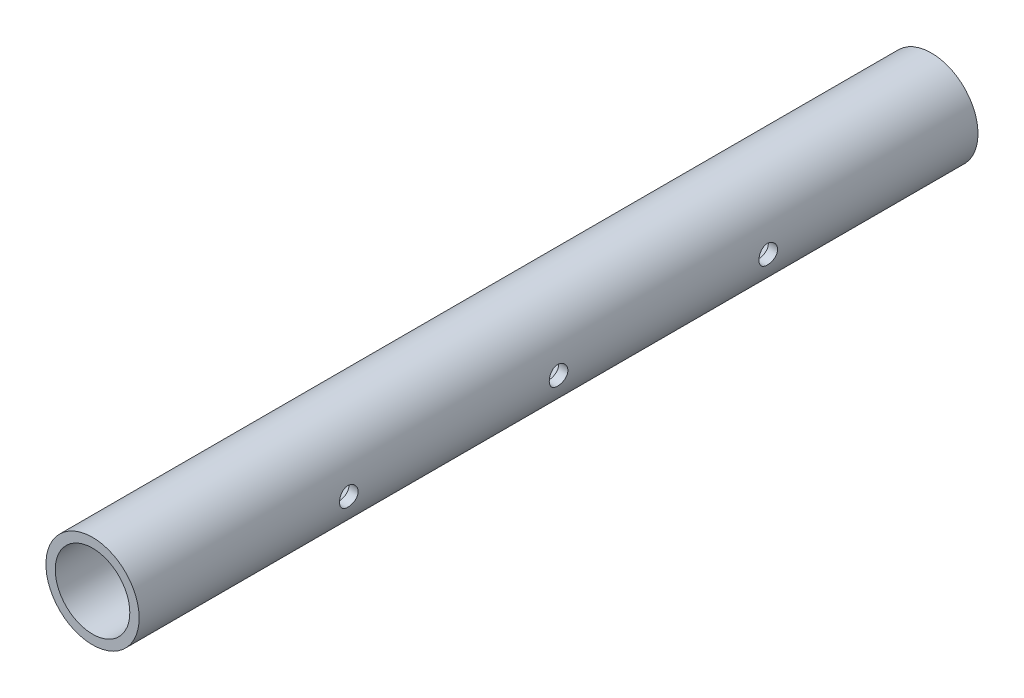
SolidWorks part; units mm, degrees
material "PVC Rigid"
ref_plane "Front Plane" through (0, 0, 0) normal (0, 0, 1) x (1, 0, 0)
ref_plane "Top Plane" through (0, 0, 0) normal (0, 1, 0) x (1, 0, 0)
ref_plane "Right Plane" through (0, 0, 0) normal (1, 0, 0) x (0, 0, -1)
sketch "Sketch1" plane through (0, 0, 0) normal (0, 0, 1) x (1, 0, 0)
  circle A0 centre (0, 0) radius 25
  circle A1 centre (0, 0) radius 20
  dimension "D1" = 50
  dimension "D2" = 5
extrude "Boss-Extrude1" add sketch "Sketch1" along normal blind 450
sketch "Sketch2" plane through (0, 0, 0) normal (1, 0, 0) x (0, 0, -1)
  line L0 (-450, 25) -> (-450, -25) construction
  line L1 (-450, 0) -> (0, 0) construction
  circle A0 centre (-337.5, 0) radius 5
  circle A1 centre (-225, 0) radius 5
  circle A2 centre (-112.5, 0) radius 5
  dimension "D1" = 10
  dimension "D3" = 10
  dimension "D5" = 10
  dimension "D2" = 112.5
  dimension "D4" = 112.5
  dimension "D6" = 112.5
extrude "Cut-Extrude2" cut sketch "Sketch2" against normal through all both and the other way through all
